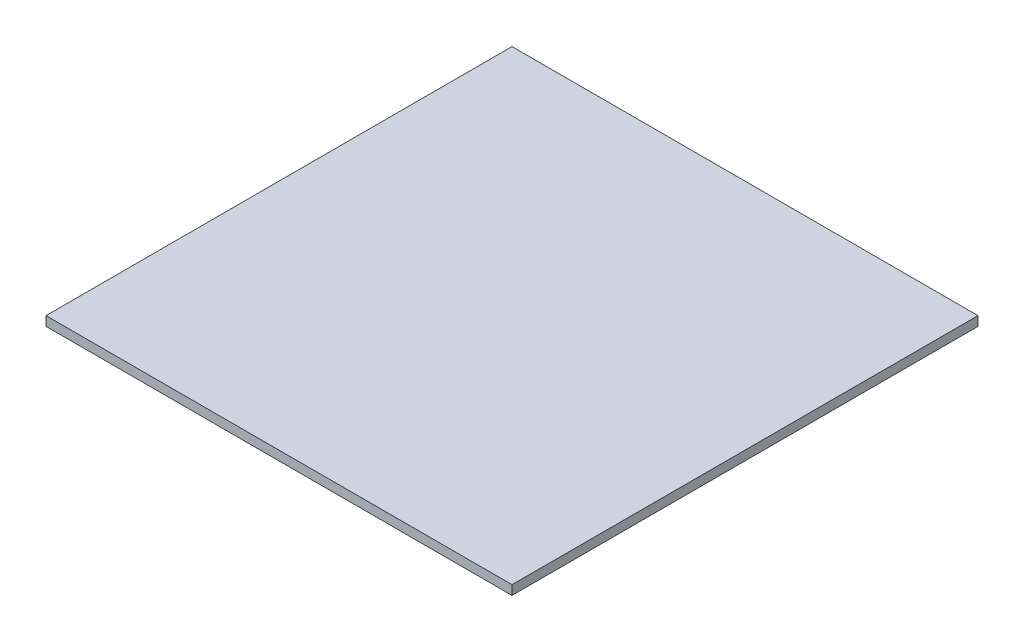
SolidWorks part; units mm, degrees
ref_plane "Plan de face" through (0, 0, 0) normal (0, 0, 1) x (1, 0, 0)
ref_plane "Plan de dessus" through (0, 0, 0) normal (0, 1, 0) x (1, 0, 0)
ref_plane "Plan de droite" through (0, 0, 0) normal (1, 0, 0) x (0, 0, -1)
sketch "Esquisse1" plane through (0, 0, 0) normal (0, 1, 0) x (1, 0, 0)
  line L1 (-88.3571, 436.634) -> (411.6429, 436.634)
  line L2 (-88.3571, 436.634) -> (-88.3571, -63.366)
  line L3 (-88.3571, -63.366) -> (411.6429, -63.366)
  line L4 (411.6429, 436.634) -> (411.6429, -63.366)
extrude "Boss.-Extru.1" add sketch "Esquisse1" along normal blind 10
